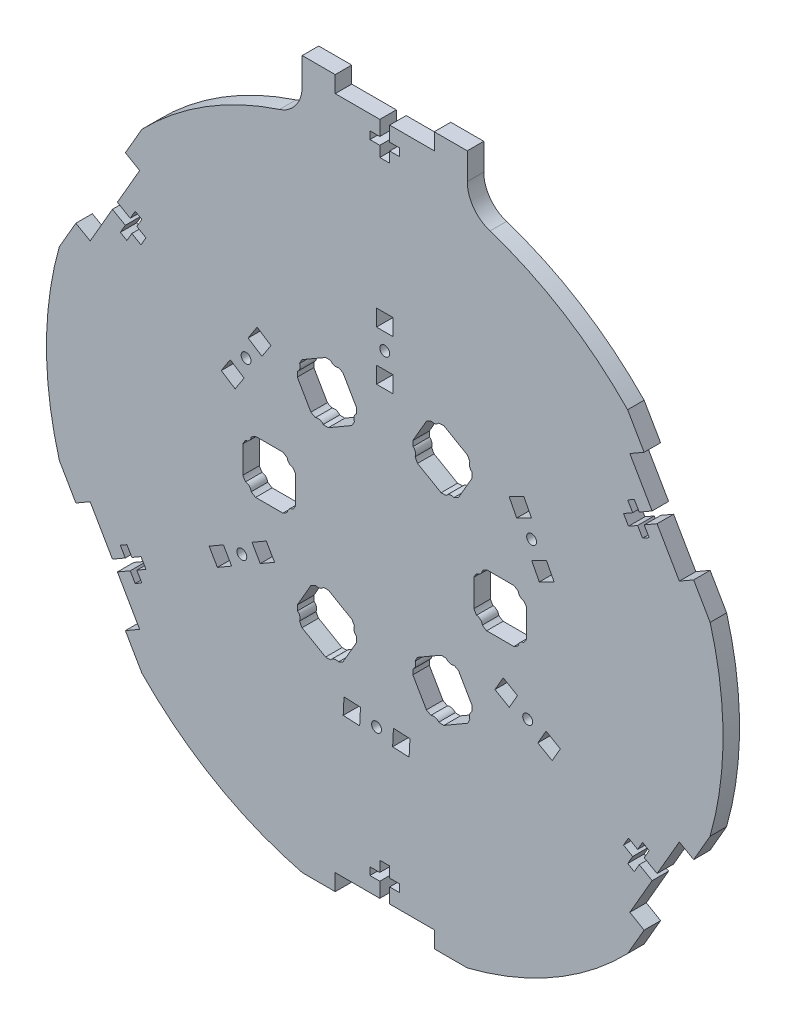
SolidWorks part; units mm, degrees
ref_plane "Plan de face" through (0, 0, 0) normal (0, 0, 1) x (1, 0, 0)
ref_plane "Plan de dessus" through (0, 0, 0) normal (0, 1, 0) x (1, 0, 0)
ref_plane "Plan de droite" through (0, 0, 0) normal (1, 0, 0) x (0, 0, -1)
sketch "Esquisse1" plane through (0, 0, 0) normal (0, 0, 1) x (1, 0, 0)
  line L0 (-21.5, 37.2391) -> (-13.5, 23.3827) construction
  line L1 (0, 0) -> (35, 0) construction
  line L2 (-25, 99.4045) -> (-25, 115)
  line L3 (25, 99.4045) -> (25, 115)
  line L4 (0, 0) -> (0, 110) construction
  circle A0 centre (0, 0) radius 102.5 construction
  arc A1 (-25, 99.4045) -> (-73.5868, 71.3529) centre (0, 0) ccw
  arc A2 (73.5868, 71.3529) -> (25, 99.4045) centre (0, 0) ccw
  arc A3 (98.5868, -28.0516) -> (98.5868, 28.0516) centre (0, 0) ccw
  arc A4 (25, -99.4045) -> (73.5868, -71.3529) centre (0, 0) ccw
  arc A5 (-73.5868, -71.3529) -> (-25, -99.4045) centre (0, 0) ccw
  arc A6 (-98.5868, 28.0516) -> (-98.5868, -28.0516) centre (0, 0) ccw
  circle A7 centre (0, 0) radius 50 construction
  circle A8 centre (0, 0) radius 35 construction
  point P3 (0, 0)
  point P7 (0, 0)
  point P8 (0, 0)
  point P13 (0.086, -0.0835)
  point P16 (0, 0)
  point P21 (0, 0)
  point P23 (0, 0)
  point P24 (0, 0)
  point P26 (0, 0)
  point P32 (0, 0)
  line B0 (80.1096, 41.0551) -> (78.1177, 39.9051)
  line B1 (75.1177, 45.1013) -> (72.3464, 43.5013)
  line B2 (73.8464, 40.9032) -> (76.6177, 42.5032)
  line B3 (78.1177, 39.9051) -> (76.6177, 42.5032)
  line B4 (82.5067, 45.9032) -> (89.2567, 34.2119)
  line B5 (93.5868, 36.7119) -> (98.5868, 28.0516)
  line B6 (93.5868, 36.7119) -> (89.2567, 34.2119)
  line B7 (81.0067, 48.5013) -> (74.2567, 60.1926)
  line B8 (74.2567, 60.1926) -> (78.5868, 62.6926)
  line B9 (78.5868, 62.6926) -> (73.5868, 71.3529)
  line B10 (82.5067, 45.9032) -> (81.0067, 48.5013) construction
  line B11 (81.0067, 48.5013) -> (77.1096, 46.2513)
  line B12 (75.1177, 45.1013) -> (73.6177, 47.6994)
  line B13 (75.6096, 48.8494) -> (77.1096, 46.2513)
  line B14 (72.3464, 43.5013) -> (73.8464, 40.9032)
  line B15 (78.6096, 43.6532) -> (80.1096, 41.0551)
  line B16 (73.6177, 47.6994) -> (75.6096, 48.8494)
  line B17 (78.6096, 43.6532) -> (82.5067, 45.9032)
  line B18 (73.0964, 42.2022) -> (81.7567, 47.2022) construction
  line B19 (75.6096, -48.8494) -> (73.6177, -47.6994)
  line B20 (76.6177, -42.5032) -> (73.8464, -40.9032)
  line B21 (72.3464, -43.5013) -> (75.1177, -45.1013)
  line B22 (73.6177, -47.6994) -> (75.1177, -45.1013)
  line B23 (81.0067, -48.5013) -> (74.2567, -60.1926)
  line B24 (78.5868, -62.6926) -> (73.5868, -71.3529)
  line B25 (78.5868, -62.6926) -> (74.2567, -60.1926)
  line B26 (82.5067, -45.9032) -> (89.2567, -34.2119)
  line B27 (89.2567, -34.2119) -> (93.5868, -36.7119)
  line B28 (93.5868, -36.7119) -> (98.5868, -28.0516)
  line B29 (81.0067, -48.5013) -> (82.5067, -45.9032) construction
  line B30 (82.5067, -45.9032) -> (78.6096, -43.6532)
  line B31 (76.6177, -42.5032) -> (78.1177, -39.9051)
  line B32 (80.1096, -41.0551) -> (78.6096, -43.6532)
  line B33 (73.8464, -40.9032) -> (72.3464, -43.5013)
  line B34 (77.1096, -46.2513) -> (75.6096, -48.8494)
  line B35 (78.1177, -39.9051) -> (80.1096, -41.0551)
  line B36 (77.1096, -46.2513) -> (81.0067, -48.5013)
  line B37 (73.0964, -42.2022) -> (81.7567, -47.2022) construction
  line B38 (-4.5, -89.9045) -> (-4.5, -87.6045)
  line B39 (1.5, -87.6045) -> (1.5, -84.4045)
  line B40 (-1.5, -84.4045) -> (-1.5, -87.6045)
  line B41 (-4.5, -87.6045) -> (-1.5, -87.6045)
  line B42 (-1.5, -94.4045) -> (-15, -94.4045)
  line B43 (-15, -99.4045) -> (-25, -99.4045)
  line B44 (-15, -99.4045) -> (-15, -94.4045)
  line B45 (1.5, -94.4045) -> (15, -94.4045)
  line B46 (15, -94.4045) -> (15, -99.4045)
  line B47 (15, -99.4045) -> (25, -99.4045)
  line B48 (-1.5, -94.4045) -> (1.5, -94.4045) construction
  line B49 (1.5, -94.4045) -> (1.5, -89.9045)
  line B50 (1.5, -87.6045) -> (4.5, -87.6045)
  line B51 (4.5, -89.9045) -> (1.5, -89.9045)
  line B52 (1.5, -84.4045) -> (-1.5, -84.4045)
  line B53 (-1.5, -89.9045) -> (-4.5, -89.9045)
  line B54 (4.5, -87.6045) -> (4.5, -89.9045)
  line B55 (-1.5, -89.9045) -> (-1.5, -94.4045)
  line B56 (0, -84.4045) -> (0, -94.4045) construction
  line B57 (-80.1096, -41.0551) -> (-78.1177, -39.9051)
  line B58 (-75.1177, -45.1013) -> (-72.3464, -43.5013)
  line B59 (-73.8464, -40.9032) -> (-76.6177, -42.5032)
  line B60 (-78.1177, -39.9051) -> (-76.6177, -42.5032)
  line B61 (-82.5067, -45.9032) -> (-89.2567, -34.2119)
  line B62 (-93.5868, -36.7119) -> (-98.5868, -28.0516)
  line B63 (-93.5868, -36.7119) -> (-89.2567, -34.2119)
  line B64 (-81.0067, -48.5013) -> (-74.2567, -60.1926)
  line B65 (-74.2567, -60.1926) -> (-78.5868, -62.6926)
  line B66 (-78.5868, -62.6926) -> (-73.5868, -71.3529)
  line B67 (-82.5067, -45.9032) -> (-81.0067, -48.5013) construction
  line B68 (-81.0067, -48.5013) -> (-77.1096, -46.2513)
  line B69 (-75.1177, -45.1013) -> (-73.6177, -47.6994)
  line B70 (-75.6096, -48.8494) -> (-77.1096, -46.2513)
  line B71 (-72.3464, -43.5013) -> (-73.8464, -40.9032)
  line B72 (-78.6096, -43.6532) -> (-80.1096, -41.0551)
  line B73 (-73.6177, -47.6994) -> (-75.6096, -48.8494)
  line B74 (-78.6096, -43.6532) -> (-82.5067, -45.9032)
  line B75 (-73.0964, -42.2022) -> (-81.7567, -47.2022) construction
  line B76 (-75.6096, 48.8494) -> (-73.6177, 47.6994)
  line B77 (-76.6177, 42.5032) -> (-73.8464, 40.9032)
  line B78 (-72.3464, 43.5013) -> (-75.1177, 45.1013)
  line B79 (-73.6177, 47.6994) -> (-75.1177, 45.1013)
  line B80 (-81.0067, 48.5013) -> (-74.2567, 60.1926)
  line B81 (-78.5868, 62.6926) -> (-73.5868, 71.3529)
  line B82 (-78.5868, 62.6926) -> (-74.2567, 60.1926)
  line B83 (-82.5067, 45.9032) -> (-89.2567, 34.2119)
  line B84 (-89.2567, 34.2119) -> (-93.5868, 36.7119)
  line B85 (-93.5868, 36.7119) -> (-98.5868, 28.0516)
  line B86 (-81.0067, 48.5013) -> (-82.5067, 45.9032) construction
  line B87 (-82.5067, 45.9032) -> (-78.6096, 43.6532)
  line B88 (-76.6177, 42.5032) -> (-78.1177, 39.9051)
  line B89 (-80.1096, 41.0551) -> (-78.6096, 43.6532)
  line B90 (-73.8464, 40.9032) -> (-72.3464, 43.5013)
  line B91 (-77.1096, 46.2513) -> (-75.6096, 48.8494)
  line B92 (-78.1177, 39.9051) -> (-80.1096, 41.0551)
  line B93 (-77.1096, 46.2513) -> (-81.0067, 48.5013)
  line B94 (-73.0964, 42.2022) -> (-81.7567, 47.2022) construction
  line B95 (0, 45) -> (0, 55) construction
  line B96 (-2.5, 45) -> (-2.5, 40)
  line B97 (-2.5, 45) -> (2.5, 45)
  line B98 (2.5, 45) -> (2.5, 40)
  line B99 (-2.5, 40) -> (2.5, 40)
  line B100 (-2.5, 55) -> (-2.5, 60)
  line B101 (-2.5, 55) -> (2.5, 55)
  line B102 (2.5, 55) -> (2.5, 60)
  line B103 (-2.5, 60) -> (2.5, 60)
  line B104 (0, 50) -> (-6.2802, 50) construction
  circle B105 centre (0, 50) radius 1.5
  line B106 (-2.5, 60) -> (2.5, 55) construction
  line B107 (-2.5, 45) -> (2.5, 40) construction
  line B108 (38.9711, -22.5) -> (47.6314, -27.5) construction
  line B109 (40.2211, -20.3349) -> (35.891, -17.8349)
  line B110 (40.2211, -20.3349) -> (37.7211, -24.6651)
  line B111 (37.7211, -24.6651) -> (33.391, -22.1651)
  line B112 (35.891, -17.8349) -> (33.391, -22.1651)
  line B113 (48.8814, -25.3349) -> (53.2115, -27.8349)
  line B114 (48.8814, -25.3349) -> (46.3814, -29.6651)
  line B115 (46.3814, -29.6651) -> (50.7115, -32.1651)
  line B116 (53.2115, -27.8349) -> (50.7115, -32.1651)
  line B117 (43.3013, -25) -> (46.4414, -19.5612) construction
  circle B118 centre (43.3013, -25) radius 1.5
  line B119 (53.2115, -27.8349) -> (46.3814, -29.6651) construction
  line B120 (40.2211, -20.3349) -> (33.391, -22.1651) construction
  line B121 (-38.9711, -22.5) -> (-47.6314, -27.5) construction
  line B122 (-37.7211, -24.6651) -> (-33.391, -22.1651)
  line B123 (-37.7211, -24.6651) -> (-40.2211, -20.3349)
  line B124 (-40.2211, -20.3349) -> (-35.891, -17.8349)
  line B125 (-33.391, -22.1651) -> (-35.891, -17.8349)
  line B126 (-46.3814, -29.6651) -> (-50.7115, -32.1651)
  line B127 (-46.3814, -29.6651) -> (-48.8814, -25.3349)
  line B128 (-48.8814, -25.3349) -> (-53.2115, -27.8349)
  line B129 (-50.7115, -32.1651) -> (-53.2115, -27.8349)
  line B130 (-43.3013, -25) -> (-40.1612, -30.4388) construction
  circle B131 centre (-43.3013, -25) radius 1.5
  line B132 (-50.7115, -32.1651) -> (-48.8814, -25.3349) construction
  line B133 (-37.7211, -24.6651) -> (-35.891, -17.8349) construction
  line B134 (42.207, 27.2685) -> (46.7709, 18.3707) construction
  line B135 (44.4314, 28.4094) -> (42.1495, 32.8583)
  line B136 (44.4314, 28.4094) -> (39.9826, 26.1275)
  line B137 (39.9826, 26.1275) -> (37.7006, 30.5764)
  line B138 (42.1495, 32.8583) -> (37.7006, 30.5764)
  line B139 (48.9954, 19.5117) -> (51.2773, 15.0628)
  line B140 (48.9954, 19.5117) -> (44.5465, 17.2297)
  line B141 (44.5465, 17.2297) -> (46.8284, 12.7808)
  line B142 (51.2773, 15.0628) -> (46.8284, 12.7808)
  line B143 (44.489, 22.8196) -> (50.0769, 25.6858) construction
  circle B144 centre (44.489, 22.8196) radius 1.5
  line B145 (51.2773, 15.0628) -> (44.5465, 17.2297) construction
  line B146 (44.4314, 28.4094) -> (37.7006, 30.5764) construction
  line B147 (2.5117, -50.1866) -> (-7.476, -49.6901) construction
  line B148 (2.3876, -52.6835) -> (7.3814, -52.9317)
  line B149 (2.3876, -52.6835) -> (2.6358, -47.6896)
  line B150 (2.6358, -47.6896) -> (7.6296, -47.9379)
  line B151 (7.3814, -52.9317) -> (7.6296, -47.9379)
  line B152 (-7.6001, -52.1871) -> (-12.5939, -51.9388)
  line B153 (-7.6001, -52.1871) -> (-7.3519, -47.1932)
  line B154 (-7.3519, -47.1932) -> (-12.3457, -46.945)
  line B155 (-12.5939, -51.9388) -> (-12.3457, -46.945)
  line B156 (-2.4822, -49.9384) -> (-2.7939, -56.2108) construction
  circle B157 centre (-2.4822, -49.9384) radius 1.5
  line B158 (-12.5939, -51.9388) -> (-7.3519, -47.1932) construction
  line B159 (2.3876, -52.6835) -> (7.6296, -47.9379) construction
  line B160 (-44.7187, 22.9181) -> (-39.2949, 31.3195) construction
  line B161 (-46.819, 24.274) -> (-49.5309, 20.0734)
  line B162 (-46.819, 24.274) -> (-42.6183, 21.5622)
  line B163 (-42.6183, 21.5622) -> (-45.3302, 17.3615)
  line B164 (-49.5309, 20.0734) -> (-45.3302, 17.3615)
  line B165 (-41.3953, 32.6754) -> (-38.6834, 36.8761)
  line B166 (-41.3953, 32.6754) -> (-37.1946, 29.9635)
  line B167 (-37.1946, 29.9635) -> (-34.4827, 34.1642)
  line B168 (-38.6834, 36.8761) -> (-34.4827, 34.1642)
  line B169 (-42.0068, 27.1188) -> (-47.283, 30.525) construction
  circle B170 centre (-42.0068, 27.1188) radius 1.5
  line B171 (-38.6834, 36.8761) -> (-37.1946, 29.9635) construction
  line B172 (-46.819, 24.274) -> (-45.3302, 17.3615) construction
  line B173 (-17.9293, 39.3006) -> (-25.0707, 35.1775)
  line B174 (-26.4898, 29.8816) -> (-22.3667, 22.7402)
  line B175 (-17.0707, 21.3211) -> (-9.9293, 25.4442)
  line B176 (-8.5102, 30.7402) -> (-12.6333, 37.8816)
  arc B177 (-16.3725, 39.24) -> (-14.0119, 38.6075) centre (-14.7824, 40.4531) ccw
  arc B178 (-16.3725, 39.24) -> (-17.9293, 39.3006) centre (-17.5, 30.3109) ccw
  arc B179 (-25.0707, 35.1775) -> (-25.7966, 33.799) centre (-17.5, 30.3109) ccw
  arc B180 (-26.4291, 31.4384) -> (-25.7966, 33.799) centre (-27.6422, 33.0285) ccw
  arc B181 (-26.4291, 31.4384) -> (-26.4898, 29.8816) centre (-17.5, 30.3109) ccw
  arc B182 (-22.3667, 22.7402) -> (-20.9881, 22.0143) centre (-17.5, 30.3109) ccw
  arc B183 (-18.6275, 21.3818) -> (-20.9881, 22.0143) centre (-20.2176, 20.1687) ccw
  arc B184 (-18.6275, 21.3818) -> (-17.0707, 21.3211) centre (-17.5, 30.3109) ccw
  arc B185 (-9.9293, 25.4442) -> (-9.2034, 26.8228) centre (-17.5, 30.3109) ccw
  arc B186 (-8.5709, 29.1834) -> (-9.2034, 26.8228) centre (-7.3578, 27.5933) ccw
  arc B187 (-8.5709, 29.1834) -> (-8.5102, 30.7402) centre (-17.5, 30.3109) ccw
  arc B188 (-12.6333, 37.8816) -> (-14.0119, 38.6075) centre (-17.5, 30.3109) ccw
  line B189 (25.0707, 35.1775) -> (17.9293, 39.3006)
  line B190 (12.6333, 37.8816) -> (8.5102, 30.7402)
  line B191 (9.9293, 25.4442) -> (17.0707, 21.3211)
  line B192 (22.3667, 22.7402) -> (26.4898, 29.8816)
  arc B193 (25.7966, 33.799) -> (26.4291, 31.4384) centre (27.6422, 33.0285) ccw
  arc B194 (25.7966, 33.799) -> (25.0707, 35.1775) centre (17.5, 30.3109) ccw
  arc B195 (17.9293, 39.3006) -> (16.3725, 39.24) centre (17.5, 30.3109) ccw
  arc B196 (14.0119, 38.6075) -> (16.3725, 39.24) centre (14.7824, 40.4531) ccw
  arc B197 (14.0119, 38.6075) -> (12.6333, 37.8816) centre (17.5, 30.3109) ccw
  arc B198 (8.5102, 30.7402) -> (8.5709, 29.1834) centre (17.5, 30.3109) ccw
  arc B199 (9.2034, 26.8228) -> (8.5709, 29.1834) centre (7.3578, 27.5933) ccw
  arc B200 (9.2034, 26.8228) -> (9.9293, 25.4442) centre (17.5, 30.3109) ccw
  arc B201 (17.0707, 21.3211) -> (18.6275, 21.3818) centre (17.5, 30.3109) ccw
  arc B202 (20.9881, 22.0143) -> (18.6275, 21.3818) centre (20.2176, 20.1687) ccw
  arc B203 (20.9881, 22.0143) -> (22.3667, 22.7402) centre (17.5, 30.3109) ccw
  arc B204 (26.4898, 29.8816) -> (26.4291, 31.4384) centre (17.5, 30.3109) ccw
  line B205 (43, -4.1231) -> (43, 4.1231)
  line B206 (39.1231, 8) -> (30.8769, 8)
  line B207 (27, 4.1231) -> (27, -4.1231)
  line B208 (30.8769, -8) -> (39.1231, -8)
  arc B209 (42.1691, -5.441) -> (40.441, -7.1691) centre (42.4246, -7.4246) ccw
  arc B210 (42.1691, -5.441) -> (43, -4.1231) centre (35, 0) ccw
  arc B211 (43, 4.1231) -> (42.1691, 5.441) centre (35, 0) ccw
  arc B212 (40.441, 7.1691) -> (42.1691, 5.441) centre (42.4246, 7.4246) ccw
  arc B213 (40.441, 7.1691) -> (39.1231, 8) centre (35, 0) ccw
  arc B214 (30.8769, 8) -> (29.559, 7.1691) centre (35, 0) ccw
  arc B215 (27.8309, 5.441) -> (29.559, 7.1691) centre (27.5754, 7.4246) ccw
  arc B216 (27.8309, 5.441) -> (27, 4.1231) centre (35, 0) ccw
  arc B217 (27, -4.1231) -> (27.8309, -5.441) centre (35, 0) ccw
  arc B218 (29.559, -7.1691) -> (27.8309, -5.441) centre (27.5754, -7.4246) ccw
  arc B219 (29.559, -7.1691) -> (30.8769, -8) centre (35, 0) ccw
  arc B220 (39.1231, -8) -> (40.441, -7.1691) centre (35, 0) ccw
  line B221 (17.9293, -39.3006) -> (25.0707, -35.1775)
  line B222 (26.4898, -29.8816) -> (22.3667, -22.7402)
  line B223 (17.0707, -21.3211) -> (9.9293, -25.4442)
  line B224 (8.5102, -30.7402) -> (12.6333, -37.8816)
  arc B225 (16.3725, -39.24) -> (14.0119, -38.6075) centre (14.7824, -40.4531) ccw
  arc B226 (16.3725, -39.24) -> (17.9293, -39.3006) centre (17.5, -30.3109) ccw
  arc B227 (25.0707, -35.1775) -> (25.7966, -33.799) centre (17.5, -30.3109) ccw
  arc B228 (26.4291, -31.4384) -> (25.7966, -33.799) centre (27.6422, -33.0285) ccw
  arc B229 (26.4291, -31.4384) -> (26.4898, -29.8816) centre (17.5, -30.3109) ccw
  arc B230 (22.3667, -22.7402) -> (20.9881, -22.0143) centre (17.5, -30.3109) ccw
  arc B231 (18.6275, -21.3818) -> (20.9881, -22.0143) centre (20.2176, -20.1687) ccw
  arc B232 (18.6275, -21.3818) -> (17.0707, -21.3211) centre (17.5, -30.3109) ccw
  arc B233 (9.9293, -25.4442) -> (9.2034, -26.8228) centre (17.5, -30.3109) ccw
  arc B234 (8.5709, -29.1834) -> (9.2034, -26.8228) centre (7.3578, -27.5933) ccw
  arc B235 (8.5709, -29.1834) -> (8.5102, -30.7402) centre (17.5, -30.3109) ccw
  arc B236 (12.6333, -37.8816) -> (14.0119, -38.6075) centre (17.5, -30.3109) ccw
  line B237 (-25.0707, -35.1775) -> (-17.9293, -39.3006)
  line B238 (-12.6333, -37.8816) -> (-8.5102, -30.7402)
  line B239 (-9.9293, -25.4442) -> (-17.0707, -21.3211)
  line B240 (-22.3667, -22.7402) -> (-26.4898, -29.8816)
  arc B241 (-25.7966, -33.799) -> (-26.4291, -31.4384) centre (-27.6422, -33.0285) ccw
  arc B242 (-25.7966, -33.799) -> (-25.0707, -35.1775) centre (-17.5, -30.3109) ccw
  arc B243 (-17.9293, -39.3006) -> (-16.3725, -39.24) centre (-17.5, -30.3109) ccw
  arc B244 (-14.0119, -38.6075) -> (-16.3725, -39.24) centre (-14.7824, -40.4531) ccw
  arc B245 (-14.0119, -38.6075) -> (-12.6333, -37.8816) centre (-17.5, -30.3109) ccw
  arc B246 (-8.5102, -30.7402) -> (-8.5709, -29.1834) centre (-17.5, -30.3109) ccw
  arc B247 (-9.2034, -26.8228) -> (-8.5709, -29.1834) centre (-7.3578, -27.5933) ccw
  arc B248 (-9.2034, -26.8228) -> (-9.9293, -25.4442) centre (-17.5, -30.3109) ccw
  arc B249 (-17.0707, -21.3211) -> (-18.6275, -21.3818) centre (-17.5, -30.3109) ccw
  arc B250 (-20.9881, -22.0143) -> (-18.6275, -21.3818) centre (-20.2176, -20.1687) ccw
  arc B251 (-20.9881, -22.0143) -> (-22.3667, -22.7402) centre (-17.5, -30.3109) ccw
  arc B252 (-26.4898, -29.8816) -> (-26.4291, -31.4384) centre (-17.5, -30.3109) ccw
  line B253 (-43, 4.1231) -> (-43, -4.1231)
  line B254 (-39.1231, -8) -> (-30.8769, -8)
  line B255 (-27, -4.1231) -> (-27, 4.1231)
  line B256 (-30.8769, 8) -> (-39.1231, 8)
  arc B257 (-42.1691, 5.441) -> (-40.441, 7.1691) centre (-42.4246, 7.4246) ccw
  arc B258 (-42.1691, 5.441) -> (-43, 4.1231) centre (-35, 0) ccw
  arc B259 (-43, -4.1231) -> (-42.1691, -5.441) centre (-35, 0) ccw
  arc B260 (-40.441, -7.1691) -> (-42.1691, -5.441) centre (-42.4246, -7.4246) ccw
  arc B261 (-40.441, -7.1691) -> (-39.1231, -8) centre (-35, 0) ccw
  arc B262 (-30.8769, -8) -> (-29.559, -7.1691) centre (-35, 0) ccw
  arc B263 (-27.8309, -5.441) -> (-29.559, -7.1691) centre (-27.5754, -7.4246) ccw
  arc B264 (-27.8309, -5.441) -> (-27, -4.1231) centre (-35, 0) ccw
  arc B265 (-27, 4.1231) -> (-27.8309, 5.441) centre (-35, 0) ccw
  arc B266 (-29.559, 7.1691) -> (-27.8309, 5.441) centre (-27.5754, 7.4246) ccw
  arc B267 (-29.559, 7.1691) -> (-30.8769, 8) centre (-35, 0) ccw
  arc B268 (-39.1231, 8) -> (-40.441, 7.1691) centre (-35, 0) ccw
  line B269 (4.5, 105.5) -> (4.5, 103.2)
  line B270 (-1.5, 103.2) -> (-1.5, 100)
  line B271 (1.5, 100) -> (1.5, 103.2)
  line B272 (4.5, 103.2) -> (1.5, 103.2)
  line B273 (1.5, 110) -> (15, 110)
  line B274 (15, 115) -> (25, 115)
  line B275 (15, 115) -> (15, 110)
  line B276 (-1.5, 110) -> (-15, 110)
  line B277 (-15, 110) -> (-15, 115)
  line B278 (-15, 115) -> (-25, 115)
  line B279 (1.5, 110) -> (-1.5, 110) construction
  line B280 (-1.5, 110) -> (-1.5, 105.5)
  line B281 (-1.5, 103.2) -> (-4.5, 103.2)
  line B282 (-4.5, 105.5) -> (-1.5, 105.5)
  line B283 (-1.5, 100) -> (1.5, 100)
  line B284 (1.5, 105.5) -> (4.5, 105.5)
  line B285 (-4.5, 103.2) -> (-4.5, 105.5)
  line B286 (1.5, 105.5) -> (1.5, 110)
  line B287 (0, 100) -> (0, 110) construction
sketch_block_instance "Insert M3 Large plots ep 5mm-3"
sketch_block "Insert M3 Large plots ep 5mm"
sketch_block_instance "Decoupe Insert M3-5"
sketch_block "Decoupe Insert M3" parameters "D1"=9, "D2"=3, "D3"=2.3, "D4"=4.5, "D5"=10
sketch_block_instance "Insert M3 Large plots ep 5mm-4"
sketch_block_instance "Insert M3 Large plots ep 5mm-5"
sketch_block_instance "Insert M3 Large plots ep 5mm-6"
sketch_block_instance "Insert M3 Large plots ep 5mm-7"
sketch_block_instance "Trou M3 plots 5mm-52"
sketch_block "Trou M3 plots 5mm" parameters "D2"=3, "D1"=5, "D3"=5, "D4"=8
sketch_block_instance "Trou M3 plots 5mm-54"
sketch_block_instance "Trou M3 plots 5mm-55"
sketch_block_instance "Trou M3 plots 5mm-56"
sketch_block_instance "Trou M3 plots 5mm-57"
sketch_block_instance "Trou M3 plots 5mm-58"
sketch_block_instance "Insert_Penetrateur_Wetlink_M10_4.5mm-1"
sketch_block "Insert_Penetrateur_Wetlink_M10_4.5mm"
sketch_block_instance "Insert_Penetrateur_Wetlink_M10_4.5mm-3"
sketch_block_instance "Insert_Penetrateur_Wetlink_M10_4.5mm-4"
sketch_block_instance "Insert_Penetrateur_Wetlink_M10_4.5mm-5"
sketch_block_instance "Insert_Penetrateur_Wetlink_M10_4.5mm-6"
sketch_block_instance "Insert_Penetrateur_Wetlink_M10_4.5mm-7"
sketch_block_instance "Insert M3 Large plots ep 5mm-8" parameters "D1"=142.1423, "D4"=116.4845, "D7"=66.3726, "D2"=144.9205, "D3"=6, "D5"=3, "D6"=3, "D8"=6
extrude "Boss.-Extru.1" add sketch "Esquisse1" along normal blind 5
fillet "Congé1" radius 10 2 edges at (-25, 99.4045, 2.5) (25, 99.4045, 2.5)
